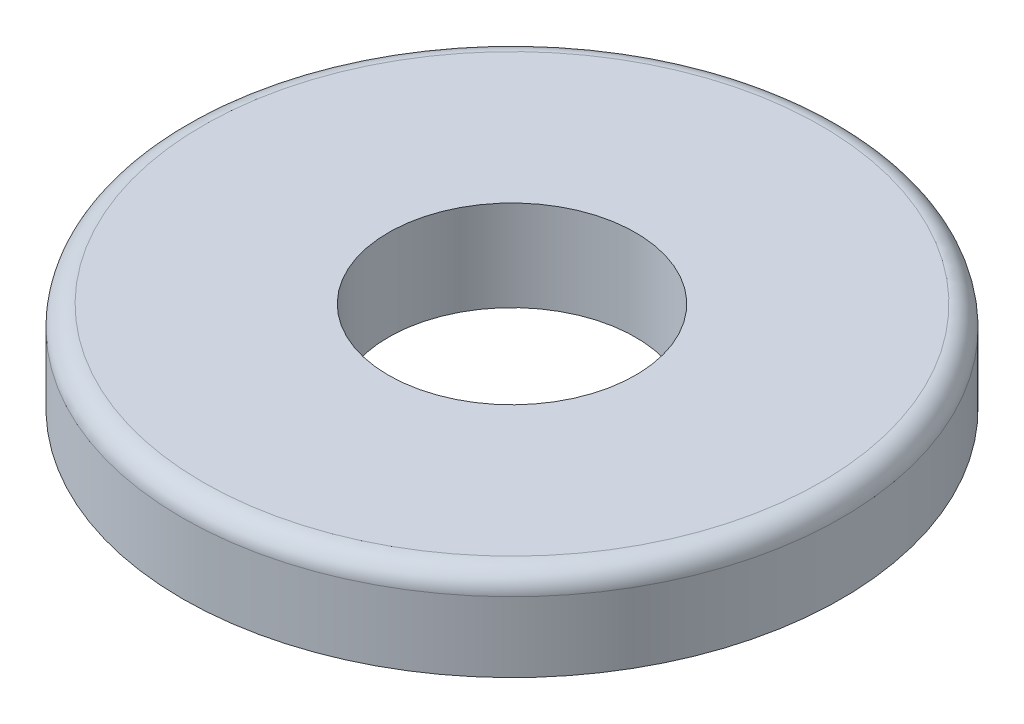
SolidWorks part; units mm, degrees
ref_plane "Alzado" through (0, 0, 0) normal (0, 0, 1) x (1, 0, 0)
ref_plane "Planta" through (0, 0, 0) normal (0, 1, 0) x (1, 0, 0)
ref_plane "Vista lateral" through (0, 0, 0) normal (1, 0, 0) x (0, 0, -1)
sketch "Croquis base" plane through (0, 0, 0) normal (0, 1, 0) x (1, 0, 0)
  circle A0 centre (0, 0) radius 4
  dimension "D1" = 8
extrude "Saliente-Extruir3" add sketch "Croquis base" along normal blind 1.1
sketch "Croquis barreno" plane through (0, 1.1, 0) normal (0, 1, 0) x (1, 0, 0)
  circle A0 centre (0, 0) radius 1.5
  dimension "D1" = 3
extrude "Cortar-Extruir1" cut sketch "Croquis barreno" against normal through all
fillet "Redondeo1" radius 0.25 1 edges at (0, 1.1, 4)
